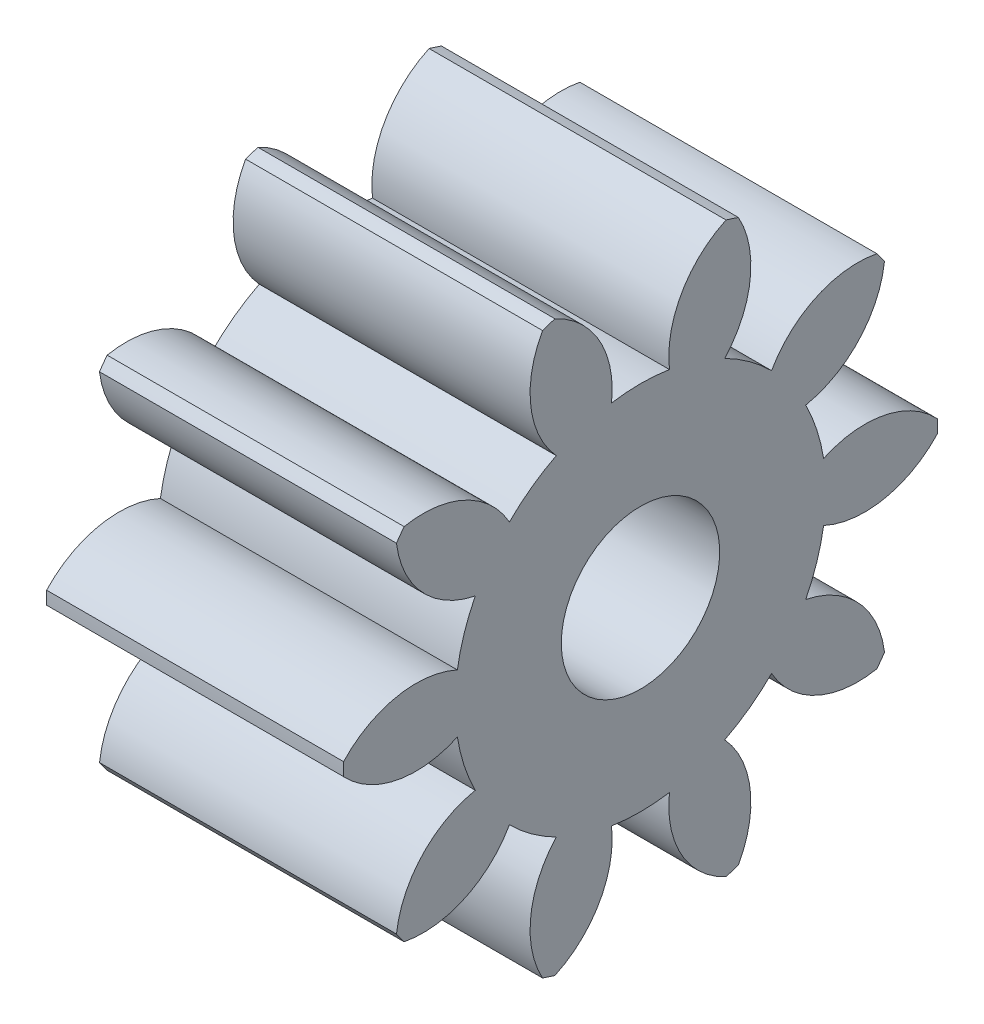
SolidWorks part; units mm, degrees
material "Простая углеродистая сталь"
ref_plane "Plane1" through (0, 0, 0) normal (0, 0, 1) x (1, 0, 0)
ref_plane "Plane2" through (0, 0, 0) normal (0, 1, 0) x (1, 0, 0)
ref_plane "Plane3" through (0, 0, 0) normal (1, 0, 0) x (0, 0, -1)
sketch "HoldingSke" plane through (0, 0, 0) normal (0, 1, 0) x (1, 0, 0)
  line L0 (0, 0) -> (3.9392, -0.6946)
  line L1 (-15, 0) -> (100, 0) construction
  line L2 (0, 0) -> (-2.1039, 2.3779)
  line L3 (0, 0) -> (-11.863, 4.5341)
  line L4 (0, 0) -> (8.5048, 1.4996)
  line L5 (0, 0) -> (-46.8476, -17.4728)
  line L6 (0, 0) -> (-1.2434, -0.839)
  line L7 (-2.1039, 2.3779) -> (8.6586, 51.2059)
  line L8 (-76.2, 54.61) -> (-76.1, 54.61)
  line L9 (-71.009, 38.7566) -> (-53.1078, 45.2721)
  line L10 (-76.2, 71.12) -> (104.1128, 71.12)
  line L11 (0, 0) -> (-1.5, 0)
  line L12 (-76.2, 101.6) -> (-76.192, 101.6)
  line L13 (24.9733, 27.94) -> (52.9518, 28.4284)
  line L14 (24.9733, 27.94) -> (24.9743, 27.94)
  line L15 (24.9733, 27.94) -> (100.4006, 29.5858)
  line L16 (-63.627, -0.25) -> (-12.827, -0.25)
  circle A0 centre (0, 0) radius 0.4
  circle A1 centre (0, 0) radius 0.9365
  circle A2 centre (0, 0) radius 37.5
  circle A3 centre (0, 0) radius 0.4
  dimension "MHD" = 1.873
  dimension "Hub_dia" = 75
  dimension "Bore" = 0.8
  dimension "MBD" = 0.8
  dimension "Num_teeth" = 10
  dimension "Pitch" = 4
  dimension "Overall_len" = 50
  dimension "Show_teeth" = 10
  dimension "Thickness" = 1.5
  dimension "OAL" = 50.0001
  dimension "T_dim" = 0.1
  dimension "Ap" = 20
  dimension "H" = 19.05
  dimension "Pitch_radius" = 180.3128
  dimension "Width" = 1.5
  dimension "Backlash" = 0.008
  dimension "Addendum_fac" = 1
  dimension "Dedendum_fac" = 1.25
  dimension "Clearance_fac" = 0.25
  dimension "Dedendum_add" = 0.001
  dimension "Module" = 0.25
sketch "BasProSke" plane through (0, 0, 0) normal (0, 1, 0) x (1, 0, 0)
  line L0 (-10, 0) -> (60, 0) construction
  line L1 (0, 0) -> (0, 1.5)
  line L2 (0, 0) -> (1.5, 0)
  line L3 (1.5, 0) -> (1.5, 1.5)
  line L4 (1.5, 1.5) -> (0, 1.5)
  dimension "Thickness" = 1.5
  dimension "Diameter" = 3
revolve "Base-Revolve" add sketch "BasProSke" angle 360 about L0
sketch "TooCutSke" plane through (0, 0, 0) normal (1, 0, 0) x (0, 0, -1)
  line L1 (0, 0) -> (0, 107) construction
  line L2 (0, 0) -> (-0.2095, 1.2323) construction
  line L3 (0, 0) -> (-0.7644, 2.3524) construction
  line L4 (-0.2095, 1.2323) -> (-0.3822, 1.1762) construction
  arc A0 (0.1463, 0.925) -> (-0.1463, 0.925) centre (0, 0) ccw
  arc A1 (0.4686, 1.4516) -> (-0.4686, 1.4516) centre (0, 0) ccw
  circle A2 centre (0, 0) radius 1.25 construction
  circle A3 centre (0, 0) radius 1.1746 construction
  arc A4 (-0.1463, 0.925) -> (-0.4686, 1.4516) centre (-0.6429, 0.983) ccw
  arc A5 (0.4686, 1.4516) -> (0.1463, 0.925) centre (0.6429, 0.983) ccw
  dimension "Root_dia" = 1.873
  dimension "Overcut_dia" = 3.0508
  dimension "Pitch_dia" = 2.5
  dimension "Base_dia" = 2.3492
  dimension "Flank_rad" = 0.5
  dimension "Half_ang" = 18
  dimension "Half_CT" = 0.1815
extrude "ToothCut" cut sketch "TooCutSke" along normal through all
fillet "Breaks" [suppressed] radius 0.005
fillet "RootFillets" [suppressed] radius 0.0635
pattern_circular "TeethCuts" count 10 every 36 about axis through (-10, 0, 0) along (1, 0, 0) of "ToothCut", "RootFillets", "Breaks"
sketch "HubNeaOneSke" plane through (0, 0, 0) normal (-1, 0, 0) x (0, 0, 1)
  circle A0 centre (0, 0) radius 0.9365
  dimension "Diameter" = 1.873
extrude "HubNearOne" [suppressed] add sketch "HubNeaOneSke" along normal blind 48.5001
sketch "HubNeaBotSke" plane through (0, 0, 0) normal (-1, 0, 0) x (0, 0, 1)
  circle A0 centre (0, 0) radius 0.9365
  dimension "Diameter" = 1.873
extrude "HubNearBoth" [suppressed] add sketch "HubNeaBotSke" along normal blind 24.25
ref_plane "FarPln" through (1.5, 0, 0) normal (1, 0, 0) x (0, 0, -1)
sketch "HubFarSke" plane through (1.5, 0, 0) normal (1, 0, 0) x (0, 0, -1)
  circle A0 centre (0, 0) radius 0.9365
  dimension "Diameter" = 1.873
extrude "HubFar" [suppressed] add sketch "HubFarSke" along normal blind 24.25
sketch "BorSke" plane through (0, 0, 0) normal (1, 0, 0) x (0, 0, -1)
  circle A0 centre (0, 0) radius 0.4
  dimension "Diameter" = 0.8
extrude "Bore" cut sketch "BorSke" along normal mid plane 100.0001
sketch "KeySke" plane through (0, 0, 0) normal (1, 0, 0) x (0, 0, -1)
  line L0 (-0.05, 0) -> (-0.05, 0.5)
  line L1 (-0.05, 0.5) -> (0.05, 0.5)
  line L2 (0.05, 0.5) -> (0.05, 0)
  line L3 (0, 0) -> (0, 34) construction
  line L4 (-0.05, 0) -> (0.05, 0)
  dimension "Offset" = 0.5
  dimension "Width" = 0.1
extrude "Keyway" [suppressed] cut sketch "KeySke" along normal mid plane 100.0001
pattern_circular "Keyway2" [suppressed] count 2 every 90 about axis through (-10, 0, 0) along (1, 0, 0)
equation "' \"Module@HoldingSke\" = 6.35"
equation "' \"Num_teeth@HoldingSke\" = 12"
equation "' \"Ap@HoldingSke\" =  20"
equation "' \"Ap@HoldingSke\" = 20"
equation "' \"Width@HoldingSke\" = 0.5 * 25.4"
equation "' \"Hub_dia@HoldingSke\"= 1 * 25.4"
equation "' \"Hub_dia@HoldingSke\" = 1 * 25.4"
equation "' \"Overall_len@HoldingSke\" = 1.0 * 25.4"
equation "' \"Bore@HoldingSke\" = 0.75 * 25.4"
equation "' \"T_dim@HoldingSke\" = 0.1 * 25.4"
equation "' \"Width@KeySke\" = 0.25 * 25.4"
equation "' \"Show_teeth@HoldingSke\" = 13"
equation "' \"Backlash@HoldingSke\" = 0.009 * 25.4"
equation "' \"Addendum_fac@HoldingSke\" = 1.0"
equation "' \"Dedendum_fac@HoldingSke\" = 1.25"
equation "' \"Dedendum_add@HoldingSke\" = 0.00005 * 25.4"
equation "' \"Clearance_fac@HoldingSke\" = 0.25"
equation "\"Pitch@HoldingSke\" = 1 / \"Module@HoldingSke\""
equation "\"Overcut_dia@TooCutSke\" = (\"Num_teeth@HoldingSke\" + 2 * \"Addendum_fac@HoldingSke\") / \"Pitch@HoldingSke\" + 0.002 * 25.4"
equation "\"Pitch_dia@TooCutSke\" = \"Num_teeth@HoldingSke\" / \"Pitch@HoldingSke\""
equation "\"Base_dia@TooCutSke\" = \"Num_teeth@HoldingSke\" / \"Pitch@HoldingSke\" * cos((\"Ap@HoldingSke\"  * 3.14159265 / 180))"
equation "\"Root_dia@TooCutSke\" = (\"Num_teeth@HoldingSke\" + 2) / \"Pitch@HoldingSke\" - 2 * (\"Addendum_fac@HoldingSke\" + \"Dedendum_fac@HoldingSke\") / \"Pitch@HoldingSke\" - \"Dedendum_add@HoldingSke\" * 2"
equation "\"Half_ang@TooCutSke\" = 180 / \"Num_teeth@HoldingSke\""
equation "\"Half_CT@TooCutSke\" = \"Num_teeth@HoldingSke\" / \"Pitch@HoldingSke\" * sin((3.14159265 / 2 / \"Num_teeth@HoldingSke\")) / 2 - 7 * \"Backlash@HoldingSke\" / 4"
equation "\"Flank_rad@TooCutSke\" = \"Num_teeth@HoldingSke\" / \"Pitch@HoldingSke\" / 5"
equation "\"Radius@RootFillets\" = \"Clearance_fac@HoldingSke\" / \"Pitch@HoldingSke\" + \"Dedendum_add@HoldingSke\""
equation "\"Break_rad@Breaks\" = 0.02 / \"Pitch@HoldingSke\""
equation "\"Thickness@HoldingSke\" = \"Width@HoldingSke\""
equation "\"OAL@HoldingSke\" = \"Thickness@HoldingSke\""
equation "\"MHD@HoldingSke\" = (\"Num_teeth@HoldingSke\" + 2) / \"Pitch@HoldingSke\" - 2 * (\"Addendum_fac@HoldingSke\" + \"Dedendum_fac@HoldingSke\")  / \"Pitch@HoldingSke\" - \"Dedendum_add@HoldingSke\" * 2"
equation "\"MBD@HoldingSke\" = (\"Num_teeth@HoldingSke\" + 2) / \"Pitch@HoldingSke\" - 2 * (\"Addendum_fac@HoldingSke\" + \"Dedendum_fac@HoldingSke\")  / \"Pitch@HoldingSke\" - \"Dedendum_add@HoldingSke\" * 2 - 0.002 * 25.4"
equation "\"MHD@HoldingSke\" = ((sgn( \"MHD@HoldingSke\" - \"Hub_dia@HoldingSke\" )-1)*( \"MHD@HoldingSke\" - \"Hub_dia@HoldingSke\" ))/-2+ \"Hub_dia@HoldingSke\""
equation "\"MBD@HoldingSke\" = ((sgn( \"MBD@HoldingSke\" - \"Bore@HoldingSke\" )-1)*( \"MBD@HoldingSke\" - \"Bore@HoldingSke\" ))/-2+ \"Bore@HoldingSke\""
equation "\"OAL@HoldingSke\" = ((sgn( \"OAL@HoldingSke\" - \"Overall_len@HoldingSke\" )+1)*( \"OAL@HoldingSke\" - \"Overall_len@HoldingSke\" ))/2 + \"Overall_len@HoldingSke\" + 0.000002 * 25.4"
equation "\"Num_teeth@TeethCuts\" = int( \"Show_teeth@HoldingSke\" ) + 1"
equation "\"Num_teeth@TeethCuts\" = ((sgn( \"Num_teeth@TeethCuts\" - \"Num_teeth@HoldingSke\" )-1)*( \"Num_teeth@TeethCuts\" - \"Num_teeth@HoldingSke\" ))/-2+ \"Num_teeth@HoldingSke\""
equation "\"Num_teeth@TeethCuts\" = ((sgn( \"Num_teeth@TeethCuts\" - 2.0)+1)*( \"Num_teeth@TeethCuts\" - 2.0))/2 +2.0"
equation "\"Angle@TeethCuts\" = 360.0 / \"Num_teeth@HoldingSke\""
equation "\"Diameter@BasProSke\" = (\"Num_teeth@HoldingSke\" + 2 * \"Addendum_fac@HoldingSke\") / \"Pitch@HoldingSke\""
equation "\"Thickness@BasProSke\"  = \"Thickness@HoldingSke\""
equation "' \"Fillet_rad@BasProSke\" =  \"Thickness@HoldingSke\" * 0.05"
equation "' \"Fillet_rad@BasProSke\" = \"Thickness@HoldingSke\" * 0.05"
equation "\"MHD@HoldingSke\" = ((sgn( \"MHD@HoldingSke\" - \"Root_dia@TooCutSke\" )-1)*( \"MHD@HoldingSke\" - \"Root_dia@TooCutSke\" ))/-2+ \"Root_dia@TooCutSke\""
equation "\"Diameter@HubNeaOneSke\" = \"MHD@HoldingSke\""
equation "\"Length@HubNearOne\" = \"OAL@HoldingSke\" - \"Thickness@BasProSke\""
equation "\"Diameter@HubNeaBotSke\" = \"MHD@HoldingSke\""
equation "\"Length@HubNearBoth\" = ( \"OAL@HoldingSke\" - \"Thickness@BasProSke\" ) / 2.0"
equation "\"Thickness@FarPln\" = \"Thickness@BasProSke\""
equation "\"Diameter@HubFarSke\" = \"MHD@HoldingSke\""
equation "\"Length@HubFar\" = ( \"OAL@HoldingSke\" - \"Thickness@BasProSke\" ) / 2.0"
equation "\"Diameter@BorSke\" = \"MBD@HoldingSke\""
equation "\"D1@Bore\" = \"OAL@HoldingSke\" * 2.0"
equation "\"D1@Keyway\" = \"OAL@HoldingSke\" * 2.0"
equation "\"Offset@KeySke\" = \"T_dim@HoldingSke\" + \"MBD@HoldingSke\" / 2.0"
